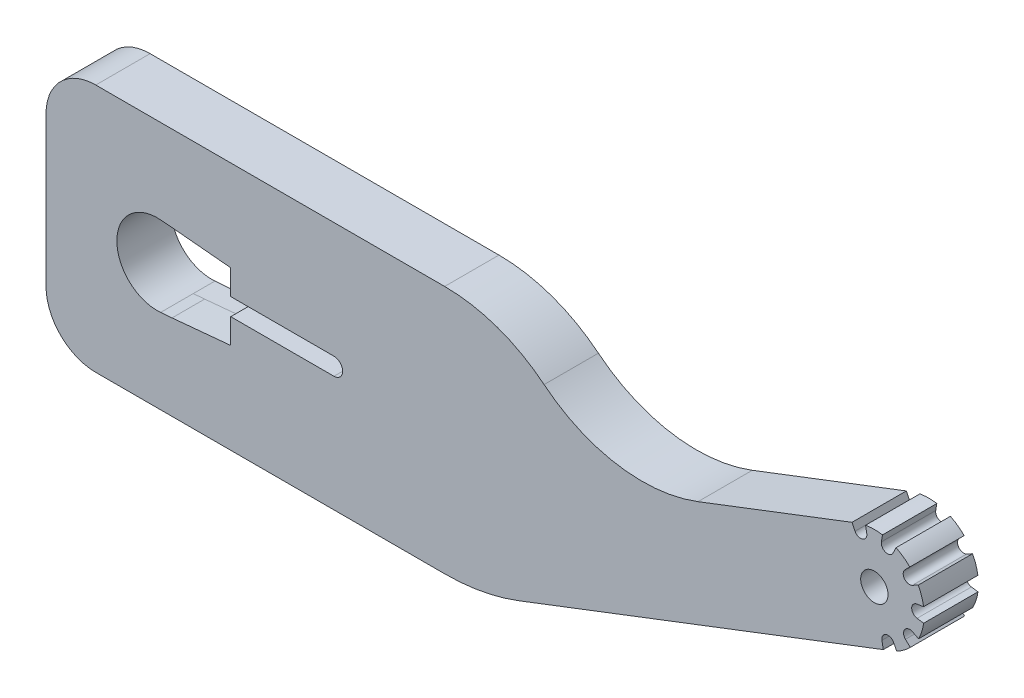
SolidWorks part; units mm, degrees
ref_plane "Alzado" through (0, 0, 0) normal (0, 0, 1) x (1, 0, 0)
ref_plane "Planta" through (0, 0, 0) normal (0, 1, 0) x (1, 0, 0)
ref_plane "Vista lateral" through (0, 0, 0) normal (1, 0, 0) x (0, 0, -1)
ref_plane "Plano1" through (0, 0, -2.5) normal (0, 0, -1) x (-1, 0, 0)
sketch "Croquis1" plane through (0, 0, -2.5) normal (0, 0, -1) x (-1, 0, 0)
  line L0 (75.5984, 14.4591) -> (75.5984, -0.4289)
  line L1 (75.5984, -0.4289) -> (48.113, -0.4289)
  line L2 (48.113, -0.4289) -> (48.113, 14.4591)
  line L3 (48.113, 14.4591) -> (75.5984, 14.4591)
  line L4 (2.1831, 10.199) -> (2.4578, 10.7478)
  line L5 (3.5335, 10.3906) -> (3.4106, 9.7045)
  line L6 (3.4106, 9.7045) -> (36.9579, -3.1731)
  line L7 (43.7782, -4.4372) -> (75.8847, -4.4372)
  line L8 (80.4656, 0.1438) -> (80.4656, 13.8865)
  line L9 (75.8847, 18.4674) -> (43.7782, 18.4674)
  line L10 (20.4656, 12.9713) -> (6.2933, 18.4116)
  line L11 (6.2933, 18.4116) -> (6.0088, 17.8432)
  line L12 (4.9331, 18.2005) -> (5.0414, 18.8046)
  line L13 (3.4841, 18.8148) -> (3.5844, 18.2093)
  line L14 (2.5042, 17.8661) -> (2.2367, 18.4184)
  line L15 (0.9708, 17.5113) -> (1.4079, 17.0804)
  line L16 (0.7357, 16.1678) -> (0.1946, 16.4574)
  line L17 (-0.2963, 14.9795) -> (0.3106, 14.8878)
  line L18 (0.3032, 13.7544) -> (-0.3048, 13.6707)
  line L19 (0.1668, 12.1864) -> (0.7116, 12.469)
  line L20 (1.3719, 11.5477) -> (0.9292, 11.1226)
  circle A0 centre (46.0516, 7.0151) radius 1.7178
  circle A1 centre (77.6598, 7.0151) radius 1.7178
  circle A2 centre (4.2333, 14.2955) radius 1.2598
  arc A3 (2.4578, 10.7478) -> (3.5335, 10.3906) centre (2.9699, 10.4916) cw
  arc A4 (36.9579, -3.1731) -> (43.7782, -4.4372) centre (43.7782, 14.5942) ccw
  arc A5 (75.8847, -4.4372) -> (80.4656, 0.1438) centre (75.8847, 0.1438) ccw
  arc A6 (80.4656, 13.8865) -> (75.8847, 18.4674) centre (75.8847, 13.8865) ccw
  arc A7 (43.7782, 18.4674) -> (34.6271, 15.2216) centre (43.7782, 3.9444) ccw
  arc A8 (34.6271, 15.2216) -> (20.4656, 12.9713) centre (25.5998, 26.3464) cw
  arc A9 (6.0088, 17.8432) -> (4.9331, 18.2005) centre (5.4968, 18.0995) cw
  arc A10 (5.0414, 18.8046) -> (3.4841, 18.8148) centre (4.2333, 14.2955) ccw
  arc A11 (3.5844, 18.2093) -> (2.5042, 17.8661) centre (3.0195, 18.1156) cw
  arc A12 (2.2367, 18.4184) -> (0.9708, 17.5113) centre (4.2333, 14.2955) ccw
  arc A13 (1.4079, 17.0804) -> (0.7357, 16.1678) centre (1.006, 16.6726) cw
  arc A14 (0.1946, 16.4574) -> (-0.2963, 14.9795) centre (4.2333, 14.2955) ccw
  arc A15 (0.3106, 14.8878) -> (0.3032, 13.7544) centre (0.2251, 14.3216) cw
  arc A16 (-0.3048, 13.6707) -> (0.1668, 12.1864) centre (4.2333, 14.2955) ccw
  arc A17 (0.7116, 12.469) -> (1.3719, 11.5477) centre (0.9752, 11.9607) cw
  arc A18 (0.9292, 11.1226) -> (2.1831, 10.199) centre (4.2333, 14.2955) ccw
  dimension "D1" = 60
extrude "Saliente-Extruir1" add sketch "Croquis1" against normal blind 5
sketch "Croquis2" plane through (0, 0, 2.5) normal (0, 0, 1) x (1, 0, 0)
  line L0 (-43.7782, -4.4372) -> (-75.8847, -4.4372) construction
  line L1 (-80.4656, 0.1438) -> (-80.4656, 13.8865) construction
  line L2 (-75.8847, 18.4674) -> (-43.7782, 18.4674) construction
  line L3 (-43.7782, -4.4372) -> (-75.8847, -4.4372)
  line L4 (-80.4656, 0.1438) -> (-80.4656, 13.8865)
  line L5 (-75.8847, 18.4674) -> (-43.7782, 18.4674)
  line L6 (-43.7782, 18.4674) -> (-43.7782, -4.4372)
  arc A0 (-80.4656, 0.1438) -> (-75.8847, -4.4372) centre (-75.8847, 0.1438) ccw construction
  arc A1 (-75.8847, 18.4674) -> (-80.4656, 13.8865) centre (-75.8847, 13.8865) ccw construction
  arc A2 (-80.4656, 0.1438) -> (-75.8847, -4.4372) centre (-75.8847, 0.1438) ccw
  arc A3 (-75.8847, 18.4674) -> (-80.4656, 13.8865) centre (-75.8847, 13.8865) ccw
extrude "Saliente-Extruir2" add sketch "Croquis2" against normal blind 5
sketch "Croquis3" plane through (0, 0, 2.5) normal (0, 0, 1) x (1, 0, 0)
  line L0 (-80.4656, 0.1438) -> (-80.4656, 13.8865) construction
  line L1 (-68.8656, 10.6151) -> (-63.4656, 10.1101)
  line L2 (-68.8656, 7.0151) -> (-55.0216, 7.0151) construction
  line L3 (-72.4656, 7.0151) -> (-72.4656, 2.1317) construction
  line L4 (-68.8656, 3.4151) -> (-63.4656, 3.9201)
  line L5 (-63.4656, 10.1101) -> (-63.4656, 3.9201)
  arc A0 (-68.8656, 10.6151) -> (-68.8656, 3.4151) centre (-68.8656, 7.0151) ccw
  point P4 (-80.4656, 7.0151)
  dimension "D1" = 7.2
  dimension "D2" = 8
  dimension "D3" = 9
  dimension "D4" = 6.19
extrude "Cortar-Extruir1" cut sketch "Croquis3" against normal blind 5
sketch "Croquis4" plane through (0, 0, 2.5) normal (0, 0, 1) x (1, 0, 0)
  line L0 (-80.4656, 0.1438) -> (-80.4656, 13.8865) construction
  line L1 (-54.7786, 9.6084) -> (-69.9133, 10.7)
  line L2 (-54.7786, 4.4219) -> (-69.9133, 3.3302)
  arc A0 (-54.7786, 4.4219) -> (-54.7786, 9.6084) centre (-54.9656, 7.0151) ccw
  arc A1 (-69.9133, 10.7) -> (-69.9133, 3.3302) centre (-70.247, 7.0151) ccw
  circle A2 centre (-68.8656, 7.0151) radius 3.6
  circle A6 centre (-68.8656, 7.0151) radius 3.6 construction
  point P5 (-80.4656, 7.0151)
  arc M2 (-68.8656, 3.4151) -> (-68.8656, 10.6151) centre (-68.8656, 7.0151) cw
  dimension "D1" = 5.2
  dimension "D3" = 3.7
  dimension "D2" = 16.5
extrude "Cortar-Extruir2" cut sketch "Croquis4" against normal blind 2 contours L2 A0 L1 M2 | A1 M2
sketch "Sketch2" plane through (0, 0, 0.5) normal (0, 0, 1) x (1, 0, 0)
  line L0 (-69.9133, 10.7) -> (-68.8656, 10.6151)
  line L1 (-69.9133, 3.3302) -> (-68.8656, 3.4151)
  arc A0 (-69.9133, 10.7) -> (-69.9133, 3.3302) centre (-70.247, 7.0151) ccw construction
  arc A1 (-69.9133, 10.7) -> (-69.9133, 3.3302) centre (-70.247, 7.0151) ccw
  arc A2 (-68.8656, 10.6151) -> (-68.8656, 3.4151) centre (-68.8656, 7.0151) ccw construction
  arc A3 (-68.8656, 10.6151) -> (-68.8656, 3.4151) centre (-68.8656, 7.0151) ccw
extrude "Cut-Extrude2" cut sketch "Sketch2" against normal through all
sketch "Sketch5" plane through (0, 0, 0.5) normal (0, 0, 1) x (1, 0, 0)
  line L0 (-63.4656, 10.1101) -> (-63.4656, 3.9201) construction
  line L1 (-63.4656, 7.8151) -> (-53.9656, 7.8151)
  line L2 (-53.9656, 6.2151) -> (-63.4656, 6.2151)
  line L3 (-63.4656, 6.2151) -> (-63.4656, 7.8151)
  circle A0 centre (-53.9656, 7.0151) radius 0.8 construction
  circle A1 centre (-63.4656, 7.0151) radius 0.8 construction
  arc A3 (-53.9656, 7.8151) -> (-53.9656, 6.2151) centre (-53.9656, 7.0151) cw
  arc A6 (-54.7786, 4.4219) -> (-54.7786, 9.6084) centre (-54.9656, 7.0151) ccw construction
  dimension "D1" = 1.6
  dimension "D2" = 1.6
  dimension "D3" = 0.8
extrude "Cut-Extrude5" cut sketch "Sketch5" against normal through all
mirror "Mirror1" about plane through (-4.2333, 14.2955, -2.5) normal (0, 0, -1) of bodies 113
delete or keep bodies "Body-Delete/Keep 1" type delete bodies bodies 113
equation "\"D2@Sketch5\"=\"D1@Sketch5\""
